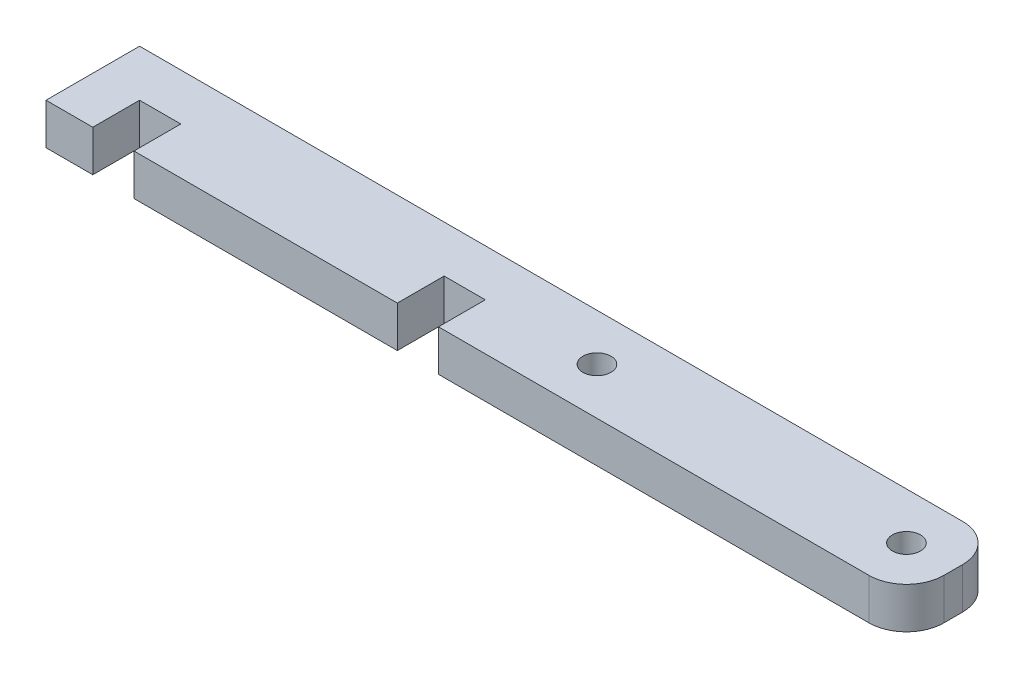
SolidWorks part; units mm, degrees
ref_plane "Front Plane" through (0, 0, 0) normal (0, 0, 1) x (1, 0, 0)
ref_plane "Top Plane" through (0, 0, 0) normal (0, 1, 0) x (1, 0, 0)
ref_plane "Right Plane" through (0, 0, 0) normal (1, 0, 0) x (0, 0, -1)
sketch "Sketch1" plane through (0, 0, 0) normal (0, 1, 0) x (1, 0, 0)
  line L0 (0, 0) -> (3.175, 0)
  line L1 (58.3819, 0) -> (58.3819, 6.35)
  line L2 (58.3819, 6.35) -> (0, 6.35)
  line L3 (0, 6.35) -> (0, 0)
  line L4 (3.175, 0) -> (3.175, 3.175)
  line L5 (3.175, 3.175) -> (5.969, 3.175)
  line L6 (5.969, 3.175) -> (5.969, 0)
  line L7 (23.8379, 0) -> (23.8379, 3.175)
  line L8 (23.8379, 3.175) -> (26.6319, 3.175)
  line L9 (26.6319, 3.175) -> (26.6319, 0)
  line L10 (5.969, 0) -> (23.8379, 0)
  line L11 (26.6319, 0) -> (58.3819, 0)
  line L13 (3.175, 32.004) -> (3.175, -48.006) construction
  line L14 (5.969, 32.004) -> (5.969, -48.006) construction
  line L15 (23.8379, 16.51) -> (23.8379, -17.272) construction
  line L16 (26.6319, 16.51) -> (26.6319, -17.272) construction
  dimension "D1" = 3.175
  dimension "D2" = 6.35
  dimension "D3" = 31.75
extrude "Boss-Extrude1" add sketch "Sketch1" along normal blind 2.794
sketch "Sketch2" plane through (0, 2.794, 0) normal (0, 1, 0) x (1, 0, 0)
  line L0 (58.3819, 0) -> (58.3819, 6.35) construction
  circle A0 centre (55.2069, 3.175) radius 0.9525
  circle A1 centre (34.2069, 3.175) radius 0.9525
  point P6 (58.3819, 3.175)
  dimension "D1" = 1.905
  dimension "D2" = 21
  dimension "D3" = 3.175
extrude "Cut-Extrude1" cut sketch "Sketch2" against normal through all
fillet "Fillet2" radius 2.54 2 edges at (58.3819, 1.397, 0) (58.3819, 1.397, -6.35)
equation "\"D1@Boss-Extrude1\"=\"thick@assy.sldasm\""
